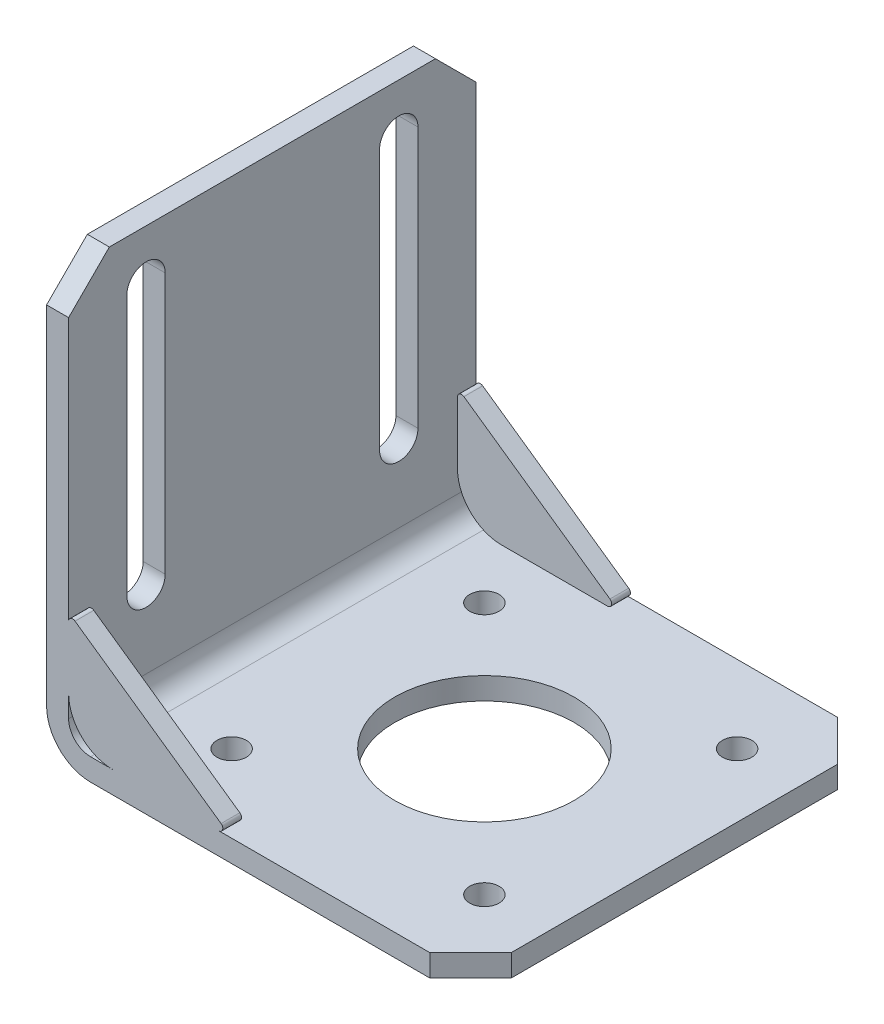
SolidWorks part; units mm, degrees
ref_plane "Front Plane" through (0, 0, 0) normal (0, 0, 1) x (1, 0, 0)
ref_plane "Top Plane" through (0, 0, 0) normal (0, 1, 0) x (1, 0, 0)
ref_plane "Right Plane" through (0, 0, 0) normal (1, 0, 0) x (0, 0, -1)
sketch "Sketch1" plane through (0, 0, 0) normal (0, 0, 1) x (1, 0, 0)
  line L0 (0, 53) -> (0, 5.4)
  line L1 (5.4, 0) -> (52, 0)
  line L2 (2.7, 53) -> (2.7, 5.4)
  line L3 (5.4, 2.7) -> (52, 2.7)
  line L4 (0, 53) -> (2.7, 53)
  line L5 (52, 2.7) -> (52, 0)
  arc A0 (5.4, 0) -> (0, 5.4) centre (5.4, 5.4) cw
  arc A1 (5.4, 2.7) -> (2.7, 5.4) centre (5.4, 5.4) cw
  point P7 (0, 0)
  dimension "D3" = 5.4
  dimension "D1" = 52
  dimension "D2" = 53
  dimension "D4" = 2.7
extrude "Boss-Extrude1" add sketch "Sketch1" along normal mid plane 50
sketch "Sketch3" plane through (0, 2.7, 0) normal (0, 1, 0) x (1, 0, 0)
  line L0 (5.4, -25) -> (52, 25) construction
  line L1 (52, 25) -> (52, -25) construction
  line L2 (52, -25) -> (5.4, 25) construction
  line L3 (13.2, 15.5) -> (13.2, -15.5) construction
  line L4 (13.2, -15.5) -> (44.2, -15.5) construction
  line L5 (44.2, -15.5) -> (44.2, 15.5) construction
  line L6 (44.2, 15.5) -> (13.2, 15.5) construction
  line L8 (13.2, -15.5) -> (44.2, 15.5) construction
  line L9 (13.2, 15.5) -> (44.2, -15.5) construction
  circle A0 centre (28.7, 0) radius 11
  circle A1 centre (44.2, 15.5) radius 1.8
  circle A2 centre (44.2, -15.5) radius 1.8
  circle A3 centre (13.2, -15.5) radius 1.8
  circle A4 centre (13.2, 15.5) radius 1.8
  dimension "D1" = 22
  dimension "D3" = 3.6
  dimension "D2" = 31
extrude "Cut-Extrude1" cut sketch "Sketch3" against normal blind 50
chamfer "Chamfer1" distance 5 angle 45 4 edges at (1.35, 53, -25) (1.35, 53, 25) (52, 1.35, 25) (52, 1.35, -25)
sketch "Sketch4" plane through (2.7, 0, 0) normal (1, 0, 0) x (0, 0, -1)
  line L0 (0, 53) -> (0, 2.7) construction
  line L1 (-20, 53) -> (20, 53) construction
  line L3 (-17.8512, 14.8199) -> (-17.8512, 46.8199)
  line L4 (-20, 2.7) -> (20, 2.7) construction
  line L5 (-13.1488, 14.8199) -> (-13.1488, 46.8199)
  line L7 (-13.7, 0) -> (-17.3, 0) construction
  line L9 (-15.5, 0) -> (-15.5, 53) construction
  line L10 (13.1488, 14.8199) -> (13.1488, 46.8199)
  line L11 (17.8512, 14.8199) -> (17.8512, 46.8199)
  arc A0 (-13.1488, 46.8199) -> (-17.8512, 46.8199) centre (-15.5, 46.8199) ccw
  arc A1 (-17.8512, 14.8199) -> (-13.1488, 14.8199) centre (-15.5, 14.8199) ccw
  arc A2 (17.8512, 14.8199) -> (13.1488, 14.8199) centre (15.5, 14.8199) cw
  arc A3 (13.1488, 46.8199) -> (17.8512, 46.8199) centre (15.5, 46.8199) cw
  dimension "D1" = 32
extrude "Cut-Extrude2" cut sketch "Sketch4" against normal blind 50
sketch "Sketch5" plane through (0, 0, -25) normal (0, 0, -1) x (-1, 0, 0)
  line L0 (-3.4867, 16.1493) -> (-21.4005, 3.6096)
  line L1 (-2.7, 5.4) -> (-2.7, 48) construction
  line L2 (-47, 2.7) -> (-5.4, 2.7) construction
  line L3 (-21.1138, 2.7) -> (-8.1, 2.7)
  line L4 (-2.7, 8.1) -> (-2.7, 15.7397)
  arc A0 (-2.7, 8.1) -> (-8.1, 2.7) centre (-8.1, 8.1) cw
  arc A1 (-2.7, 15.7397) -> (-3.4867, 16.1493) centre (-3.2, 15.7397) ccw
  arc A2 (-21.4005, 3.6096) -> (-21.1138, 2.7) centre (-21.1138, 3.2) ccw
  point P9 (-2.7, 2.7)
  point P12 (-2.7, 16.7)
  point P15 (-22.7, 2.7)
  dimension "D3" = 5.4
  dimension "D4" = 0.5
  dimension "D1" = 20
  dimension "D2" = 14
extrude "Boss-Extrude2" add sketch "Sketch5" against normal blind 2.3 separate body
mirror "Mirror2" about plane through (0, 0, 0) normal (0, 0, 1) of "Boss-Extrude2"
